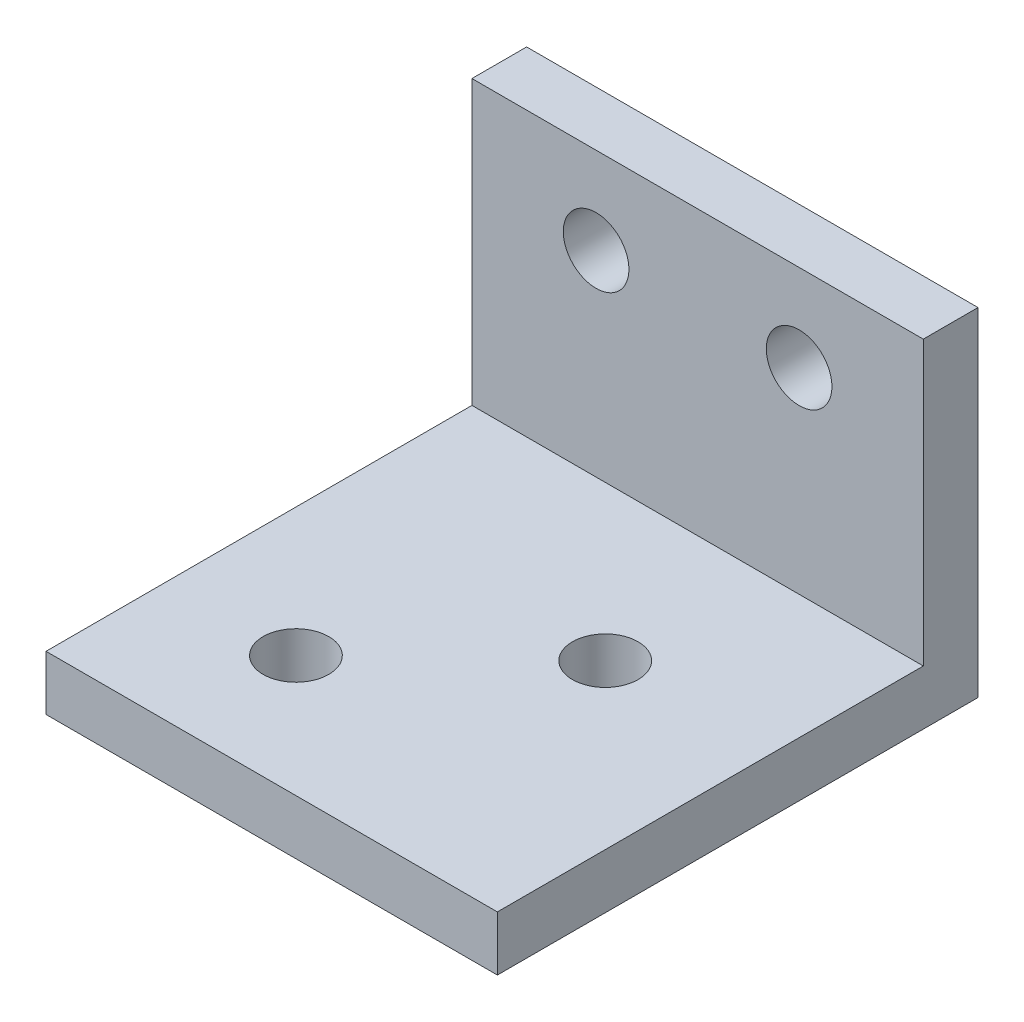
SolidWorks part; units mm, degrees
ref_plane "Front Plane" through (0, 0, 0) normal (0, 0, 1) x (1, 0, 0)
ref_plane "Top Plane" through (0, 0, 0) normal (0, 1, 0) x (1, 0, 0)
ref_plane "Right Plane" through (0, 0, 0) normal (1, 0, 0) x (0, 0, -1)
sketch "Sketch1" plane through (0, 0, 0) normal (0, 0, 1) x (1, 0, 0)
  line L2 (75.811, -27.5265) -> (94.3666, -27.5265) construction
  line L4 (64.4604, -35.464) -> (105.7172, -35.464)
  line L5 (64.4604, -35.464) -> (64.4604, -19.5889)
  line L6 (64.4604, -19.5889) -> (105.7172, -19.5889)
  line L7 (105.7172, -35.464) -> (105.7172, -19.5889)
  line L8 (64.4604, -35.464) -> (105.7172, -19.5889) construction
  line L9 (64.4604, -19.5889) -> (105.7172, -35.464) construction
  circle A0 centre (94.3666, -27.5265) radius 3
  circle A1 centre (75.811, -27.5265) radius 3
  circle A2 centre (75.811, -27.5265) radius 1.54 construction
  circle A3 centre (94.3666, -27.5265) radius 1.54 construction
  point P5 (85.0888, -27.5265)
  dimension "D1" = 6
  dimension "D2" = 6
  dimension "D3" = 18.5556
extrude "Boss-Extrude1" add sketch "Sketch1" along normal blind 5
sketch "Sketch2" plane through (0, 0, 5) normal (0, 0, 1) x (1, 0, 0)
  line L0 (64.4604, -35.464) -> (105.7172, -35.464) construction
  line L1 (64.4604, -35.464) -> (105.7172, -35.464)
  line L2 (64.4604, -35.464) -> (64.4604, -50.464)
  line L3 (64.4604, -50.464) -> (105.7172, -50.464)
  line L4 (105.7172, -35.464) -> (105.7172, -50.464)
  line L5 (105.7172, -35.464) -> (105.7172, -19.5889) construction
  line L6 (64.4604, -19.5889) -> (64.4604, -35.464) construction
  dimension "D1" = 15
extrude "Boss-Extrude3" add sketch "Sketch2" against normal up to vertex (5 mm away) up to point (64.4604, -35.464, 0)
sketch "Sketch3" plane through (0, -50.464, 0) normal (0, -1, 0) x (1, 0, 0)
  line L0 (105.7172, 5) -> (64.4604, 5) construction
  line L1 (64.4604, 5) -> (64.4604, 0) construction
  line L2 (84.796, 27.3644) -> (54.9427, 27.3644) construction
  line L3 (105.7172, 5) -> (64.4604, 5)
  line L5 (105.7172, 5) -> (64.4604, 5)
  line L6 (105.7172, 5) -> (105.7172, 43.9312)
  line L7 (105.7172, 43.9312) -> (64.4604, 43.9312)
  line L8 (64.4604, 5) -> (64.4604, 43.9312)
  line L9 (64.4604, 43.9312) -> (105.7172, 5) construction
  line L10 (84.796, 27.3644) -> (77.5055, 19.6385) construction
  circle A4 centre (76.2138, 32.8403) radius 3
  circle A5 centre (90.76, 19.1141) radius 3
  dimension "D1" = 6
  dimension "D2" = 20
extrude "Boss-Extrude5" add sketch "Sketch3" against normal blind 5
